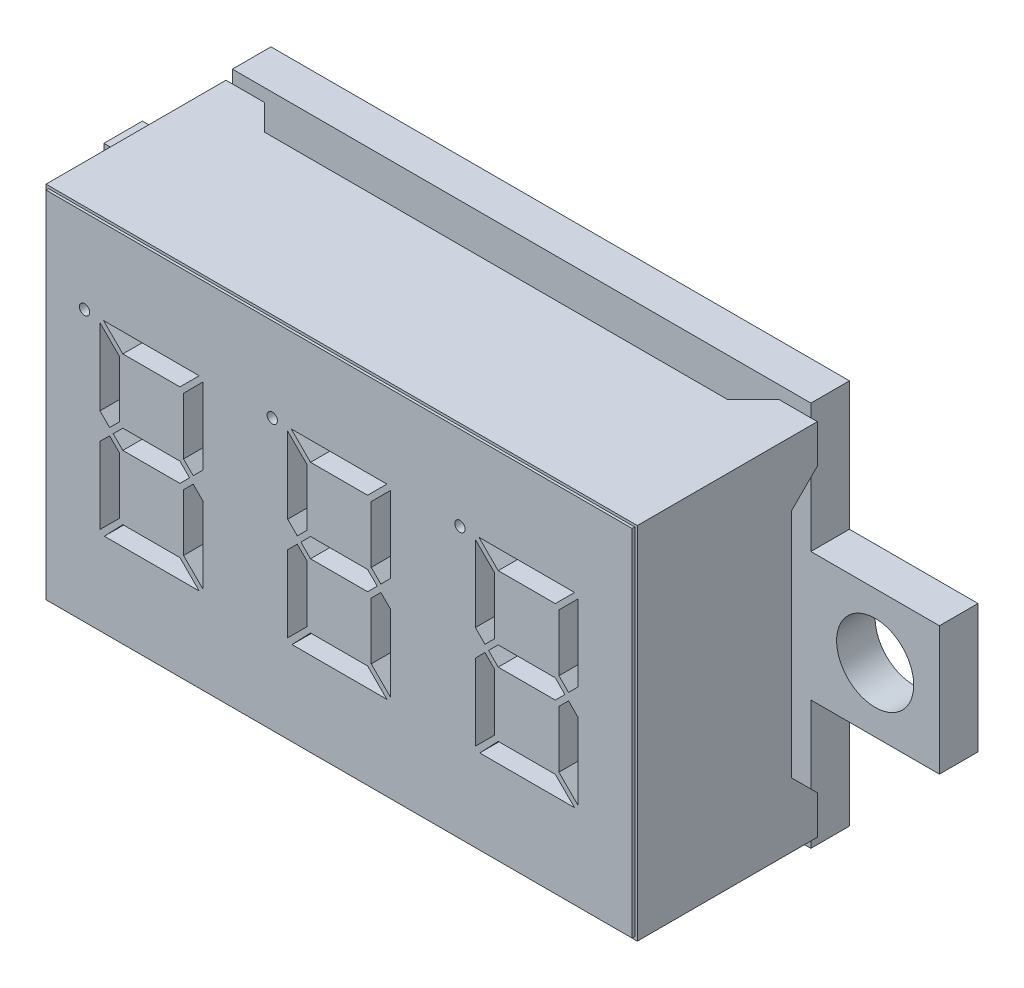
SolidWorks part; units mm, degrees
ref_plane "Front" through (0, 0, 0) normal (0, 0, 1) x (1, 0, 0)
ref_plane "Top" through (0, 0, 0) normal (0, 1, 0) x (1, 0, 0)
ref_plane "Right" through (0, 0, 0) normal (1, 0, 0) x (0, 0, -1)
sketch "草图1" plane through (0, 0, 0) normal (0, 0, 1) x (1, 0, 0)
  line L0 (0, 10) -> (0, 15)
  line L1 (0, 0) -> (22.5, 0)
  line L2 (0, 0) -> (0, 5)
  line L3 (0, 15) -> (22.5, 15)
  line L4 (22.5, 0) -> (22.5, 5)
  line L5 (0, 10) -> (-5, 10)
  line L7 (0, 5) -> (-5, 5)
  line L8 (-5, 10) -> (-5, 5)
  line L9 (22.5, 10) -> (27.5, 10)
  line L11 (22.5, 5) -> (27.5, 5)
  line L12 (27.5, 10) -> (27.5, 5)
  line L13 (22.5, 10) -> (22.5, 15)
  circle A0 centre (-2.5, 7.5) radius 1.5
  circle A1 centre (25, 7.5) radius 1.5
  dimension "D1" = 22.5
  dimension "D2" = 15
  dimension "D3" = 5
  dimension "D4" = 5
  dimension "D5" = 5
  dimension "D6" = 5
extrude "凸台-拉伸1" add sketch "草图1" along normal blind 1.5
sketch "草图2" plane through (0, 0, 1.5) normal (0, 0, 1) x (1, 0, 0)
  line L0 (0, 5) -> (0, 0) construction
  line L1 (-0.25, 14.5) -> (22.75, 14.5)
  line L2 (-0.25, 14.5) -> (-0.25, 0.5)
  line L3 (-0.25, 0.5) -> (22.75, 0.5)
  line L4 (22.75, 14.5) -> (22.75, 0.5)
  line L5 (0, 0) -> (22.5, 0) construction
  dimension "D1" = 23
  dimension "D2" = 14
  dimension "D3" = 0.25
  dimension "D4" = 0.5
extrude "凸台-拉伸2" add sketch "草图2" along normal blind 7
sketch "草图3" plane through (0, 0.5, 0) normal (0, -1, 0) x (1, 0, 0)
  line L0 (1.25, 1.5) -> (2.25, 2.5)
  line L1 (0, 1.5) -> (22.5, 1.5) construction
  line L2 (2.25, 2.5) -> (20.25, 2.5)
  line L3 (20.25, 2.5) -> (21.25, 1.5)
  line L4 (-0.25, 8.5) -> (-0.25, 1.5) construction
  line L5 (22.75, 8.5) -> (22.75, 1.5) construction
  line L6 (0, 1.5) -> (22.5, 1.5) construction
  line L7 (1.25, 1.5) -> (21.25, 1.5)
  dimension "D1" = 1.5
  dimension "D2" = 1.5
  dimension "D3" = 1
  dimension "D4" = 1
  dimension "D5" = 1
extrude "切除-拉伸3" cut sketch "草图3" against normal through all
sketch "草图4" plane through (22.75, 0, 0) normal (1, 0, 0) x (0, 0, -1)
  line L0 (-1.5, 2) -> (-2.5, 3)
  line L1 (-1.5, 0.5) -> (-1.5, 5) construction
  line L2 (-2.5, 3) -> (-2.5, 12)
  line L3 (-2.5, 12) -> (-1.5, 13)
  line L4 (-1.5, 10) -> (-1.5, 14.5) construction
  line L5 (-8.5, 0.5) -> (-1.5, 0.5) construction
  line L6 (-8.5, 14.5) -> (-1.5, 14.5) construction
  line L7 (-1.5, 2) -> (-1.5, 13)
  dimension "D1" = 1.5
  dimension "D2" = 1.5
  dimension "D3" = 1
  dimension "D4" = 1
  dimension "D5" = 1
extrude "切除-拉伸5" cut sketch "草图4" against normal through all
ref_plane "基准面1" through (0, 0, -1) normal (0, 0, -1) x (-1, 0, 0)
sketch "草图6" plane through (0, 0, -1) normal (0, 0, -1) x (-1, 0, 0)
  line L0 (0, 5) -> (0, 0) construction
  line L1 (-4.5, 2) -> (-5, 2)
  line L2 (-4.5, 2) -> (-4.5, 2.5)
  line L3 (-4.5, 2.5) -> (-5, 2.5)
  line L4 (-5, 2) -> (-5, 2.5)
  line L5 (0, 0) -> (-22.5, 0) construction
  line L6 (-22.5, 15) -> (0, 15) construction
  line L7 (-7, 2) -> (-7.5, 2)
  line L8 (-7, 2) -> (-7, 2.5)
  line L9 (-7, 2.5) -> (-7.5, 2.5)
  line L10 (-7.5, 2) -> (-7.5, 2.5)
  line L11 (-9.5, 2) -> (-10, 2)
  line L12 (-9.5, 2) -> (-9.5, 2.5)
  line L13 (-9.5, 2.5) -> (-10, 2.5)
  line L14 (-10, 2) -> (-10, 2.5)
  line L15 (-12, 2) -> (-12.5, 2)
  line L16 (-12, 2) -> (-12, 2.5)
  line L17 (-12, 2.5) -> (-12.5, 2.5)
  line L18 (-12.5, 2) -> (-12.5, 2.5)
  line L19 (-14.5, 2) -> (-15, 2)
  line L20 (-14.5, 2) -> (-14.5, 2.5)
  line L21 (-14.5, 2.5) -> (-15, 2.5)
  line L22 (-15, 2) -> (-15, 2.5)
  line L23 (-17, 2) -> (-17.5, 2)
  line L24 (-17, 2) -> (-17, 2.5)
  line L25 (-17, 2.5) -> (-17.5, 2.5)
  line L26 (-17.5, 2) -> (-17.5, 2.5)
  line L27 (-17.5, 12.5) -> (-17, 12.5)
  line L28 (-17.5, 12.5) -> (-17.5, 13)
  line L29 (-17.5, 13) -> (-17, 13)
  line L30 (-17, 12.5) -> (-17, 13)
  line L32 (-15, 12.5) -> (-14.5, 12.5)
  line L33 (-15, 12.5) -> (-15, 13)
  line L34 (-15, 13) -> (-14.5, 13)
  line L35 (-14.5, 12.5) -> (-14.5, 13)
  line L36 (-12.5, 12.5) -> (-12, 12.5)
  line L37 (-12.5, 12.5) -> (-12.5, 13)
  line L38 (-12.5, 13) -> (-12, 13)
  line L39 (-12, 12.5) -> (-12, 13)
  line L40 (-10, 12.5) -> (-9.5, 12.5)
  line L41 (-10, 12.5) -> (-10, 13)
  line L42 (-10, 13) -> (-9.5, 13)
  line L43 (-9.5, 12.5) -> (-9.5, 13)
  line L44 (-7.5, 12.5) -> (-7, 12.5)
  line L45 (-7.5, 12.5) -> (-7.5, 13)
  line L46 (-7.5, 13) -> (-7, 13)
  line L47 (-7, 12.5) -> (-7, 13)
  dimension "D1" = 0.5
  dimension "D2" = 0.5
  dimension "D3" = 4.5
  dimension "D4" = 2
  dimension "D5" = 0.5
  dimension "D6" = 2
  dimension "D7" = 0.5
  dimension "D8" = 2
  dimension "D9" = 0.5
  dimension "D10" = 2
  dimension "D11" = 0.5
  dimension "D12" = 2
  dimension "D13" = 0.5
  dimension "D14" = 2
  dimension "D15" = 0.5
  dimension "D16" = 2
extrude "凸台-拉伸3" add sketch "草图6" against normal blind 7
sketch "草图8" plane through (0, 0, 0) normal (0, 0, -1) x (-1, 0, 0)
  line L0 (-22.5, 15) -> (0, 15) construction
  line L1 (0, 15) -> (0, 10) construction
  circle A0 centre (-1, 14) radius 0.3
  circle A1 centre (-2.5, 14) radius 0.3
  circle A2 centre (-4, 14) radius 0.3
  dimension "D1" = 1
  dimension "D2" = 1
  dimension "D3" = 1.5
  dimension "D4" = 1.5
extrude "凸台-拉伸4" add sketch "草图8" along normal blind 0.5
sketch "草图9" plane through (0, 0, 8.5) normal (0, 0, 1) x (1, 0, 0)
  line L1 (22.65, 0.6) -> (-0.15, 0.6)
  line L2 (22.65, 0.6) -> (22.65, 14.4)
  line L3 (22.65, 14.4) -> (-0.15, 14.4)
  line L4 (-0.15, 0.6) -> (-0.15, 14.4)
  line L5 (22.75, 0.5) -> (22.75, 14.5) construction
  line L6 (-0.25, 0.5) -> (22.75, 0.5) construction
  line L7 (22.75, 14.5) -> (-0.25, 14.5) construction
  line L8 (-0.25, 14.5) -> (-0.25, 0.5) construction
  dimension "D1" = 0.1
  dimension "D2" = 0.1
  dimension "D3" = 0.1
  dimension "D4" = 0.1
extrude "凸台-拉伸5" add sketch "草图9" along normal blind 0.1
sketch "草图12" plane through (0, 0, 8.6) normal (0, 0, 1) x (1, 0, 0)
  line L1 (20.4086, 3.875) -> (16.7191, 3.875)
  line L2 (20.55, 4.0164) -> (20.55, 6.9836)
  line L3 (20.4086, 11.125) -> (16.6886, 11.125)
  line L5 (19.6586, 4.625) -> (17.4386, 4.625)
  line L6 (19.8, 4.7664) -> (19.8, 6.9836)
  line L7 (19.6586, 7.125) -> (17.4386, 7.125)
  line L9 (19.6586, 7.875) -> (17.4386, 7.875)
  line L10 (19.8, 8.0164) -> (19.8, 10.2336)
  line L11 (19.6586, 10.375) -> (17.4386, 10.375)
  line L12 (17.3, 8.0136) -> (17.3, 10.2336)
  line L13 (19.8, 6.9836) -> (20.175, 7.3586)
  line L27 (19.8, 4.7664) -> (20.55, 4.0164)
  line L40 (19.6586, 4.625) -> (20.4086, 3.875)
  line L41 (17.4386, 4.625) -> (16.7191, 3.875)
  line L42 (17.3, 4.7664) -> (16.55, 4.0164)
  line L43 (19.6586, 7.125) -> (20.0336, 7.5)
  line L44 (17.3, 6.9836) -> (16.9236, 7.36)
  line L45 (17.4386, 7.125) -> (17.0636, 7.5)
  line L46 (19.8, 8.0164) -> (20.175, 7.6414)
  line L47 (19.6586, 7.875) -> (20.0336, 7.5)
  line L48 (17.4386, 7.875) -> (17.0636, 7.5)
  line L49 (17.3, 8.0136) -> (16.925, 7.6386)
  line L50 (19.8, 10.2336) -> (20.55, 10.9836)
  line L51 (19.6586, 10.375) -> (20.4086, 11.125)
  line L52 (17.3, 10.2336) -> (16.55, 10.9836)
  line L53 (17.4386, 10.375) -> (16.6886, 11.125)
  line L54 (20.175, 7.6414) -> (20.55, 8.0164)
  line L55 (20.175, 7.3586) -> (20.55, 6.9836)
  line L57 (16.925, 7.6386) -> (16.55, 8.0136)
  line L61 (16.55, 8.0136) -> (16.55, 10.9836)
  line L63 (20.55, 8.0164) -> (20.55, 10.9836)
  line L67 (17.3, 4.7664) -> (17.3, 6.9836)
  line L68 (16.9236, 7.36) -> (16.5472, 6.9836)
  line L69 (16.55, 4.0164) -> (16.5472, 6.9836)
  dimension "D6" = 0.75
  dimension "D7" = 0.75
  dimension "D8" = 0.75
  dimension "D9" = 0.75
  dimension "D10" = 0.75
  dimension "D29" = 45
extrude "切除-拉伸6" cut sketch "草图12" against normal blind 1
pattern_linear "阵列(线性)1" count 3 spacing 7.3 along (-1, 0, 0) of "切除-拉伸6"
sketch "草图13" plane through (0, 0, 8.6) normal (0, 0, 1) x (1, 0, 0)
  line L0 (16.55, 10.9836) -> (16.55, 8.0136) construction
  line L1 (20.4086, 11.125) -> (16.6886, 11.125) construction
  line L2 (9.25, 10.9836) -> (9.25, 8.0136) construction
  line L3 (1.95, 10.9836) -> (1.95, 8.0136) construction
  circle A0 centre (15.95, 11.125) radius 0.2
  circle A1 centre (8.65, 11.125) radius 0.2
  circle A2 centre (1.35, 11.125) radius 0.2
  dimension "D1" = 0.6
  dimension "D3" = 0.6
  dimension "D4" = 0.6
  dimension "D2" = 0
extrude "切除-拉伸7" cut sketch "草图13" against normal blind 1
